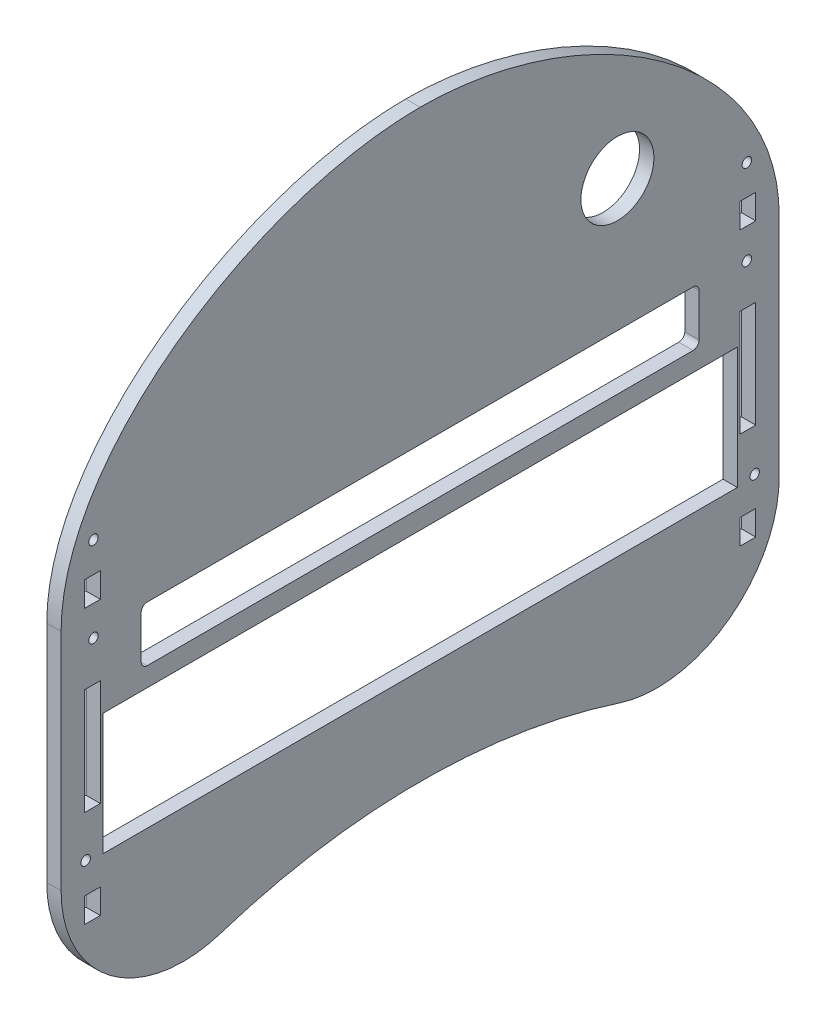
SolidWorks part; units mm, degrees
ref_plane "Front Plane" through (0, 0, 0) normal (0, 0, 1) x (1, 0, 0)
ref_plane "Top Plane" through (0, 0, 0) normal (0, 1, 0) x (1, 0, 0)
ref_plane "Right Plane" through (0, 0, 0) normal (1, 0, 0) x (0, 0, -1)
sketch "Sketch1" plane through (0, 0, 0) normal (1, 0, 0) x (0, 0, -1)
  line L0 (0, 123) -> (0, -402.9766) construction
  line L1 (-150, 8.4066) -> (-150, -102.5888) construction
  line L2 (-132.5, -30) -> (132.5, -30)
  line L3 (-116.54, 1) -> (-116.54, -22)
  line L4 (132.5, -80.8) -> (132.5, -30)
  line L5 (-132.5, -80.8) -> (-132.5, -30)
  line L6 (-116.54, 1) -> (116.54, 1)
  line L7 (136.906, -92.2288) -> (136.906, -102.5888) construction
  line L8 (-116.54, -22) -> (116.54, -22)
  line L9 (116.54, 1) -> (116.54, -22)
  line L10 (-150, 8.4066) -> (-150, -102.5888)
  line L11 (133.631, -92.2288) -> (140.181, -92.2288)
  line L12 (0, -2.4285) -> (0, -37.4285) construction
  line L13 (0, 1) -> (0, 0) construction
  line L14 (133.631, -92.2288) -> (133.631, -102.5888)
  line L15 (133.631, -102.5888) -> (140.181, -102.5888)
  line L16 (140.181, -92.2288) -> (140.181, -102.5888)
  line L17 (133.631, -97.4088) -> (140.181, -97.4088) construction
  line L18 (150, 8.4066) -> (150, -102.5888) construction
  line L19 (132.5, -80.8) -> (-132.5, -80.8)
  line L20 (133.631, -17.6258) -> (140.181, -17.6258)
  line L21 (133.631, -17.6258) -> (133.631, -62.0758)
  line L22 (136.906, -17.6258) -> (136.906, -62.0758) construction
  line L23 (133.631, -62.0758) -> (140.181, -62.0758)
  line L24 (133.631, -39.8508) -> (140.181, -39.8508) construction
  line L25 (140.181, -17.6258) -> (140.181, -62.0758)
  line L26 (140.181, 22.1679) -> (140.181, 11.8079)
  line L28 (133.631, 22.1679) -> (140.181, 22.1679)
  line L29 (133.631, 22.1679) -> (133.631, 11.8079)
  line L30 (133.631, 11.8079) -> (140.181, 11.8079)
  line L31 (133.631, 16.9879) -> (140.181, 16.9879) construction
  line L32 (136.906, 22.1679) -> (136.906, 11.8079) construction
  line L33 (150, 8.4066) -> (150, -102.5888)
  line L36 (-16.764, -82.1415) -> (16.764, -82.1415) construction
  line L38 (0, -82.1415) -> (0, -98.1122) construction
  line L43 (-136.906, 22.1679) -> (-136.906, 11.8079) construction
  line L44 (-133.631, 16.9879) -> (-140.181, 16.9879) construction
  line L45 (-133.631, -39.8508) -> (-140.181, -39.8508) construction
  line L46 (-136.906, -17.6258) -> (-136.906, -62.0758) construction
  line L47 (-133.631, -97.4088) -> (-140.181, -97.4088) construction
  line L48 (-136.906, -92.2288) -> (-136.906, -102.5888) construction
  line L53 (-133.631, 11.8079) -> (-140.181, 11.8079)
  line L54 (-133.631, 22.1679) -> (-133.631, 11.8079)
  line L55 (-133.631, 22.1679) -> (-140.181, 22.1679)
  line L56 (-16.764, -115.5568) -> (16.764, -115.5568) construction
  line L57 (16.764, -82.1415) -> (16.764, -115.5568) construction
  line L58 (-140.181, 22.1679) -> (-140.181, 11.8079)
  line L59 (-16.764, -115.5568) -> (-16.764, -82.1415) construction
  line L60 (-140.181, -17.6258) -> (-140.181, -62.0758)
  line L61 (-133.631, -62.0758) -> (-140.181, -62.0758)
  line L62 (-133.631, -17.6258) -> (-133.631, -62.0758)
  line L63 (-133.631, -17.6258) -> (-140.181, -17.6258)
  line L64 (-140.181, -92.2288) -> (-140.181, -102.5888)
  line L65 (-133.631, -102.5888) -> (-140.181, -102.5888)
  line L66 (-133.631, -92.2288) -> (-133.631, -102.5888)
  line L67 (-133.631, -92.2288) -> (-140.181, -92.2288)
  line L68 (150, -102.5888) -> (126.739, -102.5888) construction
  line L69 (121.1718, -22) -> (145.7704, -22) construction
  line L70 (-139.9293, 97.3753) -> (-139.9293, -115.9494) construction
  line L71 (139.9293, -115.9494) -> (139.9293, 89.0758) construction
  line L72 (-24.6481, 123) -> (24.6481, 123) construction
  line L73 (150, 8.4066) -> (121.1718, 8.4066) construction
  circle A0 centre (16.764, -82.1415) radius 2.54 construction
  circle A1 centre (139.7381, -79.6288) radius 1.9844
  circle A2 centre (136.4742, -0.7921) radius 1.9844
  circle A3 centre (136.4742, 34.7679) radius 1.9844
  circle A4 centre (-136.4742, 34.7679) radius 1.9844
  circle A5 centre (-136.4742, -0.7921) radius 1.9844
  circle A6 centre (-139.7381, -79.6288) radius 1.9844
  arc A8 (-150, -102.5888) -> (150, -102.5888) centre (0, 0) ccw
  circle A12 centre (-16.764, -82.1415) radius 2.54 construction
  circle A13 centre (-16.764, -115.5568) radius 2.54 construction
  circle A14 centre (16.764, -115.5568) radius 2.54 construction
  circle A15 centre (82.4, 56) radius 15.24
  arc A17 (110.1934, -144.5056) -> (-110.1934, -144.5056) centre (0, -390.7576) ccw
  spline S0 degree 3 poles (150, 8.4066) (150, 69.9923) (70.2896, 123) (0, 123) knots 0 0 0 0 1 1 1 1
  spline S1 degree 3 poles (-150, 8.4066) (-150, 69.9923) (-70.2896, 123) (0, 123) knots 0 0 0 0 1 1 1 1
  point P2 (0, -181.7263)
  point P131 (0, -80.8)
  point P132 (0, -30)
  dimension "D12" = 17.78
  dimension "D13" = 17.78
  dimension "D7" = 17.78
  dimension "D25" = 114.3967
  dimension "D17" = 17.78
  dimension "D9" = 17.553
  dimension "D24" = 10.36
  dimension "D4" = 4.406
  dimension "D5" = 50.8
  dimension "D6" = 23
  dimension "D8" = 233.08
  dimension "D10" = 33.528
  dimension "D11" = 33.4153
  dimension "D14" = 34.14
  dimension "D15" = 181.7263
  dimension "D16" = 44.45
  dimension "D18" = 55
  dimension "D19" = 150
  dimension "D20" = 132.5
  dimension "D21" = 8
  dimension "D22" = 123
  dimension "D23" = 30
  dimension "D27" = 6.55
  dimension "D30" = 150
  dimension "D31" = 6.55
  dimension "D32" = 150
extrude "Extrude1" add sketch "Sketch1" along normal blind 5.9944
fillet "Fillet3" radius 50.8 1 edges at (2.9972, -102.5888, 150)
fillet "Fillet4" radius 50.8 1 edges at (2.9972, -144.5056, 110.1934)
fillet "Fillet5" radius 50.8 1 edges at (2.9972, -144.5056, -110.1934)
fillet "Fillet6" radius 50.8 1 edges at (2.9972, -102.5888, -150)
fillet "Fillet12" radius 2.54 1 edges at (2.9972, -22, 116.54)
fillet "Fillet13" radius 2.54 1 edges at (2.9972, 1, 116.54)
fillet "Fillet14" radius 2.54 1 edges at (2.9972, 1, -116.54)
fillet "Fillet15" radius 2.54 1 edges at (2.9972, -22, -116.54)
